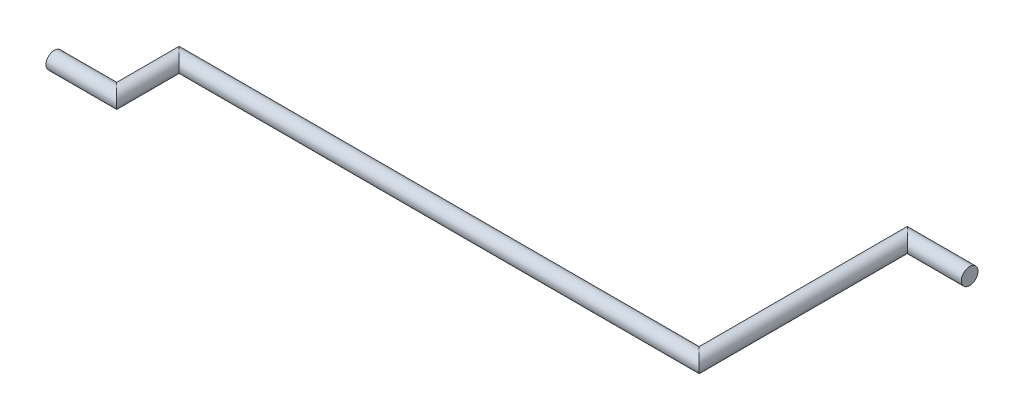
SolidWorks part; units mm, degrees
ref_plane "Front Plane" through (0, 0, 0) normal (0, 0, 1) x (1, 0, 0)
ref_plane "Top Plane" through (0, 0, 0) normal (0, 1, 0) x (1, 0, 0)
ref_plane "Right Plane" through (0, 0, 0) normal (1, 0, 0) x (0, 0, -1)
sketch "Sketch1" plane through (0, 0, 0) normal (0, 1, 0) x (1, 0, 0)
  line L0 (0, 0) -> (3, 0)
  line L1 (3, 0) -> (3, 3)
  line L2 (3, 3) -> (28, 3)
  line L3 (28, 3) -> (28, 13)
  line L4 (28, 13) -> (31, 13)
  dimension "D1" = 3
  dimension "D2" = 3
  dimension "D3" = 3
  dimension "D4" = 25
  dimension "D5" = 10
sketch "Sketch2" plane through (0, 0, 0) normal (1, 0, 0) x (0, 0, -1)
  circle A0 centre (0, 0) radius 0.4
  dimension "D1" = 0.8
sweep "Sweep1" add profiles "Sketch2" path "Sketch1"
